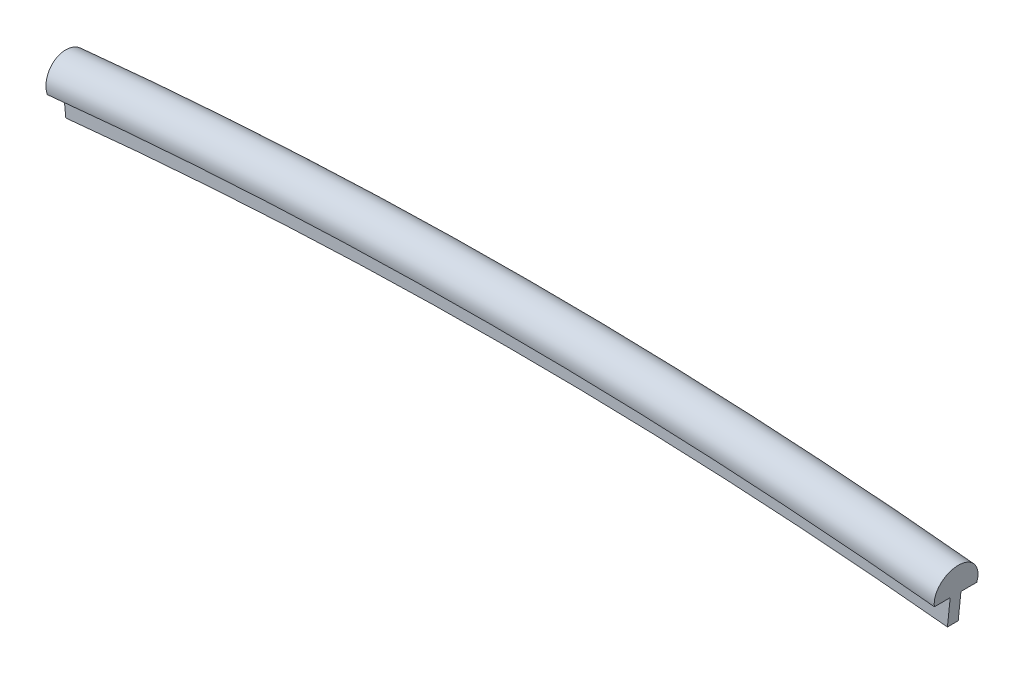
SolidWorks part; units mm, degrees
ref_plane "Front Plane" through (0, 0, 0) normal (0, 0, 1) x (1, 0, 0)
ref_plane "Top Plane" through (0, 0, 0) normal (0, 1, 0) x (1, 0, 0)
ref_plane "Right Plane" through (0, 0, 0) normal (1, 0, 0) x (0, 0, -1)
sketch "Sketch2" plane through (0, 0, 0) normal (1, 0, 0) x (0, 0, -1)
  line L0 (0, 241.3) -> (0, 0) construction
  line L2 (0, 241.3) -> (0, 239.8) construction
  line L3 (0, 239.8) -> (0.3, 239.8)
  line L4 (0, 239.8) -> (-0.3, 239.8)
  line L5 (-0.3, 239.8) -> (-0.3, 241.3)
  line L6 (0.3, 239.8) -> (0.3, 241.3)
  line L7 (0, 241.3) -> (0, 242.8) construction
  line L8 (-1.18, 241.3) -> (-0.3, 241.3)
  line L9 (0.3, 241.3) -> (1.18, 241.3)
  arc A0 (-1.18, 241.3) -> (1.18, 241.3) centre (0, 241.586) cw
  point P14 (0, 241.3)
ref_axis "Axis2" through (0, 0, 70.5976) along (0, 0, -1)
revolve "Revolve1" add sketch "Sketch2" angle 5.877 about axis through (0, 0, 70.5976) along (0, 0, -1)
